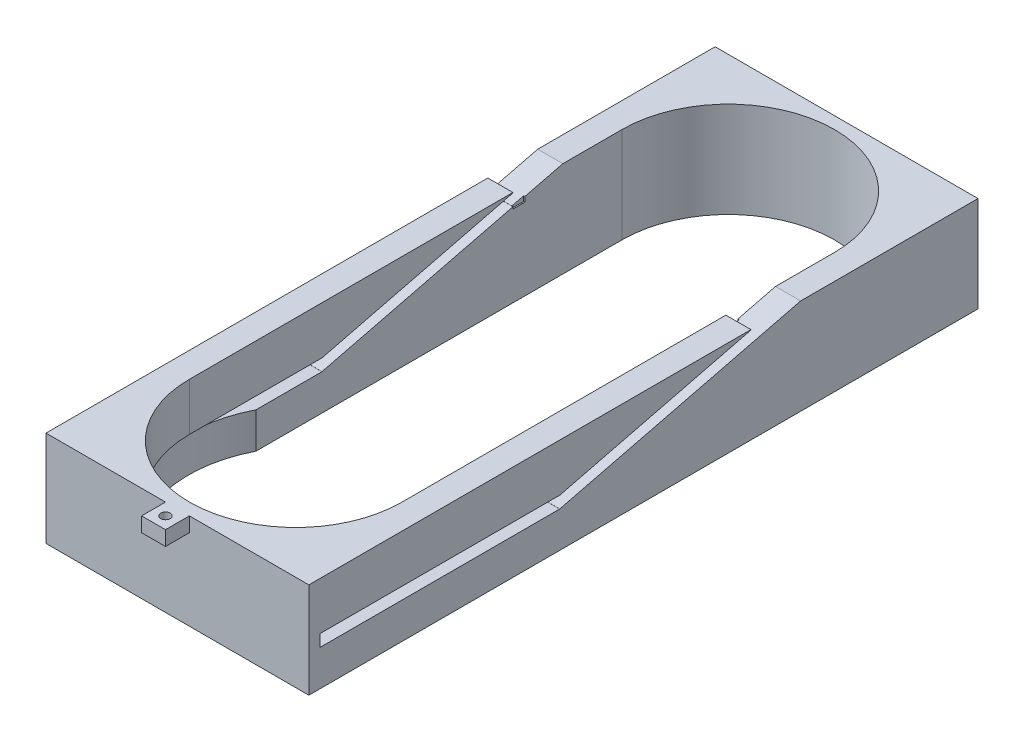
SolidWorks part; units mm, degrees
ref_plane "Front Plane" through (0, 0, 0) normal (0, 0, 1) x (1, 0, 0)
ref_plane "Top Plane" through (0, 0, 0) normal (0, 1, 0) x (1, 0, 0)
ref_plane "Right Plane" through (0, 0, 0) normal (1, 0, 0) x (0, 0, -1)
sketch "Sketch1" plane through (0, 0, 0) normal (0, 1, 0) x (1, 0, 0)
  line L0 (0, -19.4563) -> (0, 161.5437) construction
  line L1 (-55, -68.9563) -> (55, -68.9563)
  line L2 (-55, -68.9563) -> (-55, 211.0437)
  line L3 (-55, 211.0437) -> (55, 211.0437)
  line L4 (55, -68.9563) -> (55, 211.0437)
  line L5 (-44.5, -19.4563) -> (-44.5, 161.5437)
  line L6 (44.5, -19.4563) -> (44.5, 161.5437)
  arc A0 (-44.5, -19.4563) -> (44.5, -19.4563) centre (0, -19.4563) ccw
  arc A1 (44.5, 161.5437) -> (-44.5, 161.5437) centre (0, 161.5437) ccw
  point P6 (0, 71.0437)
  dimension "D3" = 10.5
  dimension "D4" = 49.5
  dimension "D5" = 49.5
  dimension "D1" = 280
  dimension "D2" = 110
  dimension "D6" = 10.5
extrude "Boss-Extrude1" add sketch "Sketch1" along normal blind 40
sketch "Sketch2" plane through (55, 0, 0) normal (1, 0, 0) x (0, 0, -1)
  line L0 (116.0437, 39.8511) -> (36.0437, 20)
  line L1 (-68.9563, 40) -> (211.0437, 40) construction
  line L2 (211.0437, 40) -> (211.0437, 0) construction
  line L3 (35.9228, 15.0015) -> (116.0437, 34.8511)
  line L4 (116.0437, 39.8511) -> (116.0437, 34.8511)
  line L5 (35.9228, 15.0015) -> (36.0437, 20)
  dimension "D1" = 95
  dimension "D2" = 20
  dimension "D3" = 80
  dimension "D4" = 5
  dimension "D6" = 5
extrude "Cut-Extrude2" cut sketch "Sketch2" against normal blind 124 contours L4 L3 L5 L0
sketch "Sketch3" plane through (0, 40, 0) normal (0, 1, 0) x (1, 0, 0)
  line L0 (55, -68.9563) -> (55, 211.0437) construction
  line L1 (55, 116.0356) -> (44.5, 116.0356)
  line L2 (55, 116.0356) -> (55, 121.0356)
  line L3 (55, 121.0356) -> (44.5, 121.0356)
  line L4 (44.5, 116.0356) -> (44.5, 121.0356)
  line L5 (44.5, -19.4563) -> (44.5, 161.5437) construction
  dimension "D1" = 5
extrude "Cut-Extrude3" cut sketch "Sketch3" against normal blind 6
sketch "Sketch4" plane through (0, 40, 0) normal (0, 1, 0) x (1, 0, 0)
  line L0 (-44.5, 161.5437) -> (-44.5, -19.4563) construction
  line L1 (-44.5, 115.9309) -> (-55, 115.9309)
  line L2 (-44.5, 115.9309) -> (-44.5, 120.9309)
  line L3 (-44.5, 120.9309) -> (-55, 120.9309)
  line L4 (-55, 115.9309) -> (-55, 120.9309)
  line L5 (-55, 211.0437) -> (-55, -68.9563) construction
  dimension "D1" = 5
extrude "Cut-Extrude4" cut sketch "Sketch4" against normal blind 6
sketch "Sketch5" plane through (55, 0, 0) normal (1, 0, 0) x (0, 0, -1)
  line L0 (116.0356, 34.8491) -> (136.8267, 40)
  line L1 (121.0356, 40) -> (211.0437, 40) construction
  line L2 (136.8267, 40) -> (116.0356, 40)
  line L3 (116.0356, 40) -> (116.0356, 34.8491)
extrude "Cut-Extrude5" cut sketch "Sketch5" against normal blind 115
sketch "Sketch6" plane through (-55, 0, 0) normal (-1, 0, 0) x (0, 0, 1)
  line L1 (-120.9309, 36.0619) -> (-115.9309, 36.0619)
  line L2 (-120.9309, 36.0619) -> (-120.9309, 34)
  line L3 (-120.9309, 34) -> (-115.9309, 34)
  line L4 (-115.9309, 36.0619) -> (-115.9309, 34)
extrude "Boss-Extrude2" add sketch "Sketch6" against normal blind 10
sketch "Sketch7" plane through (55, 0, 0) normal (1, 0, 0) x (0, 0, -1)
  line L1 (121.0356, 34) -> (116.0356, 34)
  line L2 (121.0356, 34) -> (121.0356, 36.3396)
  line L3 (121.0356, 36.3396) -> (116.0356, 36.3396)
  line L4 (116.0356, 34) -> (116.0356, 36.3396)
extrude "Boss-Extrude3" add sketch "Sketch7" against normal blind 10
sketch "Sketch8" plane through (55, 0, 0) normal (1, 0, 0) x (0, 0, -1)
  line L0 (121.0356, 36.0878) -> (116.0356, 34.8491)
  line L1 (116.0356, 34.8491) -> (116.0356, 36.3396)
  line L2 (121.0356, 36.3396) -> (116.0356, 36.3396) construction
  line L3 (116.0356, 36.3396) -> (116.0356, 34.8491) construction
  line L4 (116.0356, 36.3396) -> (121.0356, 36.3396)
  line L5 (121.0356, 36.3396) -> (121.0356, 36.0878)
extrude "Cut-Extrude6" cut sketch "Sketch8" against normal blind 128
sketch "Sketch9" plane through (-45, 0, 0) normal (1, 0, 0) x (0, 0, -1)
  line L0 (115.9309, 34.8232) -> (115.9309, 36.0619) construction
  line L1 (116.0356, 34.8491) -> (115.9309, 34.8491)
  line L2 (116.0356, 34.8491) -> (116.0356, 36.0619)
  line L3 (116.0356, 36.0619) -> (115.9309, 36.0619)
  line L4 (115.9309, 34.8491) -> (115.9309, 36.0619)
extrude "Cut-Extrude7" cut sketch "Sketch9" against normal blind 128
sketch "Sketch10" plane through (55, 0, 0) normal (1, 0, 0) x (0, 0, -1)
  line L1 (35.6536, 15.0033) -> (-64.3464, 15.0033)
  line L2 (35.6536, 15.0033) -> (35.6536, 20.0033)
  line L3 (35.6536, 20.0033) -> (-64.3464, 20.0033)
  line L4 (-64.3464, 15.0033) -> (-64.3464, 20.0033)
  dimension "D1" = 5
  dimension "D2" = 100
extrude "Cut-Extrude9" cut sketch "Sketch10" against normal blind 128
sketch "Sketch11" plane through (55, 0, 0) normal (1, 0, 0) x (0, 0, -1)
  line L1 (36.0437, 20) -> (35.6536, 20)
  line L2 (36.0437, 20) -> (36.0437, 15.0033)
  line L3 (36.0437, 15.0033) -> (35.6536, 15.0033)
  line L4 (35.6536, 20) -> (35.6536, 15.0033)
extrude "Cut-Extrude10" cut sketch "Sketch11" against normal blind 128
sketch "Sketch13" plane through (0, 0, 0) normal (0, -1, 0) x (-1, 0, 0)
  circle A0 centre (0, -14.3463) radius 50
extrude "Cut-Extrude11" cut sketch "Sketch13" against normal blind 20
sketch "Sketch14" plane through (0, 0, 68.9563) normal (0, 0, 1) x (1, 0, 0)
  line L0 (-55, 40) -> (55, 40) construction
  line L1 (-5, 40) -> (5, 40)
  line L2 (-5, 40) -> (-5, 33.9033)
  line L3 (-5, 33.9033) -> (5, 33.9033)
  line L4 (5, 40) -> (5, 33.9033)
  line L5 (-55, 40) -> (-55, 0) construction
  dimension "D1" = 10
  dimension "D2" = 50
extrude "Boss-Extrude4" add sketch "Sketch14" along normal blind 10
sketch "Sketch15" plane through (0, 40, 0) normal (0, 1, 0) x (1, 0, 0)
  line L0 (5, -78.9563) -> (-5, -78.9563) construction
  circle A0 centre (0, -73.9563) radius 2
  dimension "D1" = 5
extrude "Cut-Extrude12" cut sketch "Sketch15" against normal blind 10
